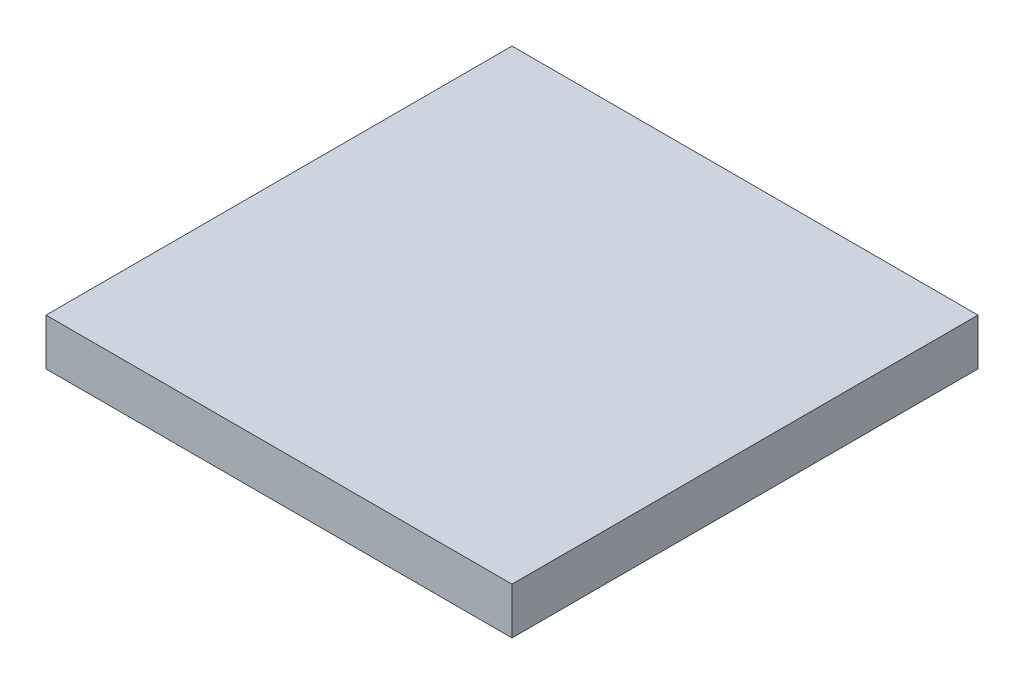
SolidWorks part; units mm, degrees
ref_plane "Front Plane" through (0, 0, 0) normal (0, 0, 1) x (1, 0, 0)
ref_plane "Top Plane" through (0, 0, 0) normal (0, 1, 0) x (1, 0, 0)
ref_plane "Right Plane" through (0, 0, 0) normal (1, 0, 0) x (0, 0, -1)
sketch "Sketch1" plane through (0, 0, 0) normal (0, 1, 0) x (1, 0, 0)
  line L1 (-63.5, -63.5) -> (63.5, -63.5)
  line L2 (-63.5, -63.5) -> (-63.5, 63.5)
  line L3 (-63.5, 63.5) -> (63.5, 63.5)
  line L4 (63.5, -63.5) -> (63.5, 63.5)
  line L5 (-63.5, -63.5) -> (63.5, 63.5) construction
  line L6 (-63.5, 63.5) -> (63.5, -63.5) construction
  point P0 (0, 0)
  dimension "D1" = 127
extrude "Boss-Extrude1" add sketch "Sketch1" along normal blind 12.7
